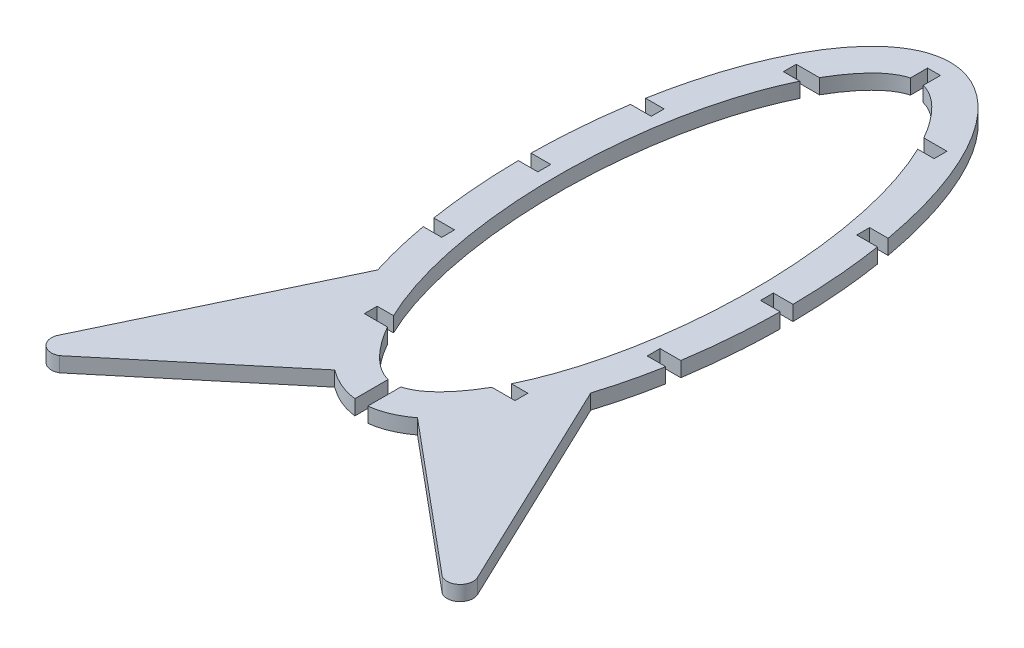
SolidWorks part; units mm, degrees
ref_plane "Front Plane" through (0, 0, 0) normal (0, 0, 1) x (1, 0, 0)
ref_plane "Top Plane" through (0, 0, 0) normal (0, 1, 0) x (1, 0, 0)
ref_plane "Right Plane" through (0, 0, 0) normal (1, 0, 0) x (0, 0, -1)
sketch "Sketch1" plane through (0, 0, 0) normal (0, 1, 0) x (1, 0, 0)
  line L2 (25.4, 0) -> (-45.1447, 0) construction
  line L3 (21.59, 0) -> (30.3971, 0) construction
  line L4 (21.59, 1.2446) -> (25.394, 1.2446)
  line L5 (21.59, 1.2446) -> (21.59, -1.2446)
  line L6 (21.59, -1.2446) -> (25.394, -1.2446)
  line L8 (37.0979, -78.485) -> (8.0291, -54.2196)
  line L9 (40.6569, -75.1899) -> (20.6588, -33.2492)
  line L10 (23.7402, 20.32) -> (29.3413, 20.32) construction
  line L11 (19.9302, 21.5646) -> (23.5224, 21.5646)
  line L12 (19.9302, 21.5646) -> (19.9302, 19.0754)
  line L13 (19.9302, 19.0754) -> (23.9434, 19.0754)
  line L19 (14.0482, 40.64) -> (-23.5224, 40.64) construction
  line L20 (0, 57.15) -> (0, 53.975) construction
  line L21 (-37.0979, -78.485) -> (-8.0291, -54.2196)
  line L22 (-14.6132, -41.8846) -> (-10.1242, -41.8846)
  line L23 (-14.6132, -41.8846) -> (-14.6132, -39.3954)
  line L24 (-14.6132, -39.3954) -> (-11.4313, -39.3954)
  line L25 (19.9302, -21.5646) -> (23.5224, -21.5646)
  line L26 (19.9302, -21.5646) -> (19.9302, -19.0754)
  line L27 (19.9302, -19.0754) -> (23.9434, -19.0754)
  line L28 (-40.6569, -75.1899) -> (-20.6588, -33.2492)
  line L29 (14.6132, 41.8846) -> (10.1242, 41.8846)
  line L30 (14.6132, 41.8846) -> (14.6132, 39.3954)
  line L31 (14.6132, 39.3954) -> (11.4313, 39.3954)
  line L32 (-19.9302, -21.5646) -> (-23.5224, -21.5646)
  line L33 (-19.9302, -21.5646) -> (-19.9302, -19.0754)
  line L34 (-19.9302, -19.0754) -> (-23.9434, -19.0754)
  line L35 (-21.59, 1.2446) -> (-21.59, -1.2446)
  line L36 (-21.59, 1.2446) -> (-25.394, 1.2446)
  line L37 (-21.59, -1.2446) -> (-25.394, -1.2446)
  line L38 (-19.9302, 21.5646) -> (-23.5224, 21.5646)
  line L39 (-19.9302, 21.5646) -> (-19.9302, 19.0754)
  line L40 (-19.9302, 19.0754) -> (-23.9434, 19.0754)
  line L41 (14.6132, -39.3954) -> (11.4313, -39.3954)
  line L42 (-14.6132, 41.8846) -> (-10.1242, 41.8846)
  line L43 (-14.6132, 41.8846) -> (-14.6132, 39.3954)
  line L44 (-14.6132, 39.3954) -> (-11.4313, 39.3954)
  line L46 (0, 39.3954) -> (0, -57.15) construction
  line L47 (14.6132, -41.8846) -> (14.6132, -39.3954)
  line L48 (14.6132, -41.8846) -> (10.1242, -41.8846)
  line L49 (1.2446, -53.975) -> (1.2446, -50.6449)
  line L50 (-1.2446, 53.975) -> (1.2446, 53.975)
  line L51 (-1.2446, 53.975) -> (-1.2446, 50.6449)
  line L53 (1.2446, 53.975) -> (1.2446, 50.6449)
  line L54 (1.2446, -53.975) -> (1.2446, -57.0814)
  line L55 (-1.2446, -53.975) -> (-1.2446, -50.6449)
  line L56 (-1.2446, -53.975) -> (-1.2446, -57.0814)
  arc A0 (37.0979, -78.485) -> (40.6569, -75.1899) centre (38.3642, -76.2831) ccw
  arc A1 (-37.0979, -78.485) -> (-40.6569, -75.1899) centre (-38.3642, -76.2831) cw
  ellipse E0 centre (0, 0) end of major axis (0, 57.15) minor radius 25.4 (-23.9434, 19.0754) -> (-25.394, 1.2446) ccw
  ellipse E1 centre (0, 0) end of major axis (0, 57.15) minor radius 25.4 (-25.394, -1.2446) -> (-23.9434, -19.0754) ccw
  ellipse E2 centre (0, 0) end of major axis (0, 57.15) minor radius 25.4 (-23.5224, -21.5646) -> (-20.6588, -33.2492) ccw
  ellipse E3 centre (0, 0) end of major axis (0, 57.15) minor radius 25.4 (23.9434, -19.0754) -> (25.394, -1.2446) ccw
  ellipse E4 centre (0, 0) end of major axis (0, 57.15) minor radius 25.4 (25.394, 1.2446) -> (23.9434, 19.0754) ccw
  ellipse E5 centre (0, 0) end of major axis (0, 57.15) minor radius 25.4 (23.5224, 21.5646) -> (-23.5224, 21.5646) ccw
  ellipse E6 centre (0, 0) end of major axis (0, 57.15) minor radius 25.4 (1.2446, -57.0814) -> (8.0291, -54.2196) ccw
  ellipse E7 centre (0, 0) end of major axis (0, 57.15) minor radius 25.4 (-8.0291, -54.2196) -> (-1.2446, -57.0814) ccw
  ellipse E8 centre (0, 0) end of major axis (0, 57.15) minor radius 25.4 (20.6588, -33.2492) -> (23.5224, -21.5646) ccw
  spline S0 degree 3 poles (10.1242, 41.8846) (9.6963, 42.6376) (8.1175, 45.2063) (5.3181, 48.5143) (2.7975, 50.1532) (1.5926, 50.559) (1.2446, 50.6449) knots -0.663564 -0.663564 -0.663564 -0.663564 -0.589049 -0.392699 -0.19635 -0.109038 -0.109038 -0.109038 -0.109038
  spline S1 degree 3 poles (1.2446, -50.6449) (1.5926, -50.559) (2.7975, -50.1532) (5.3181, -48.5143) (8.1175, -45.2063) (9.6963, -42.6376) (10.1242, -41.8846) knots -3.032554 -3.032554 -3.032554 -3.032554 -2.945243 -2.748894 -2.552544 -2.478028 -2.478028 -2.478028 -2.478028
  spline S2 degree 3 poles (-1.2446, -50.6449) (-1.5926, -50.559) (-2.7975, -50.1532) (-5.3181, -48.5143) (-8.1175, -45.2063) (-9.6963, -42.6376) (-10.1242, -41.8846) knots -3.032554 -3.032554 -3.032554 -3.032554 -2.945243 -2.748894 -2.552544 -2.478028 -2.478028 -2.478028 -2.478028
  spline S3 degree 3 poles (-10.1242, 41.8846) (-9.6963, 42.6376) (-8.1175, 45.2063) (-5.3181, 48.5143) (-2.7975, 50.1532) (-1.5926, 50.559) (-1.2446, 50.6449) knots -0.663564 -0.663564 -0.663564 -0.663564 -0.589049 -0.392699 -0.19635 -0.109038 -0.109038 -0.109038 -0.109038
  spline S4 degree 3 poles (-11.4313, -39.3954) (-11.6771, -38.8896) (-12.9878, -36.0709) (-15.1482, -30.1662) (-18.0998, -17.7755) (-19.6835, 0) (-18.0998, 17.7755) (-15.1482, 30.1662) (-12.9878, 36.0709) (-11.6771, 38.8896) (-11.4313, 39.3954) knots -2.400746 -2.400746 -2.400746 -2.400746 -2.356194 -2.159845 -1.963495 -1.570796 -1.178097 -0.981748 -0.785398 -0.740847 -0.740847 -0.740847 -0.740847
  spline S5 degree 3 poles (11.4313, -39.3954) (11.6771, -38.8896) (12.9878, -36.0709) (15.1482, -30.1662) (18.0998, -17.7755) (19.6835, 0) (18.0998, 17.7755) (15.1482, 30.1662) (12.9878, 36.0709) (11.6771, 38.8896) (11.4313, 39.3954) knots -2.400746 -2.400746 -2.400746 -2.400746 -2.356194 -2.159845 -1.963495 -1.570796 -1.178097 -0.981748 -0.785398 -0.740847 -0.740847 -0.740847 -0.740847
  point P25 (19.9302, 20.32)
  point P35 (44.1664, -82.55)
  dimension "D5" = 2.54
  dimension "D1" = 114.3
  dimension "D2" = 25.4
  dimension "D4" = 2.4892
  dimension "D6" = 3.81
  dimension "D7" = 2.4892
  dimension "D9" = 3.81
  dimension "D3" = 25.4
  dimension "D10" = 2.4892
  dimension "D8" = 2.4892
  dimension "D11" = 39.8605
  dimension "D12" = 29.2264
  dimension "D13" = 20.32
extrude "Boss-Extrude1" add sketch "Sketch1" along normal blind 2.8956
equation "\"slot_width\"= 0.098"
equation "\"slot_depth\"= 0.15"
equation "\"body_height\"= 4.5"
equation "\"fin_height\"= 1"
equation "\"gap_distance\"= 0.8"
equation "\"D1@Sketch1\"=\"body_height\""
equation "\"D4@Sketch1\"=\"slot_width\""
equation "\"D7@Sketch1\"=\"slot_width\""
equation "\"D10@Sketch1\"=\"slot_width\""
equation "\"D13@Sketch1\"=\"gap_distance\""
equation "\"D3@Sketch1\"=\"fin_height\""
equation "\"D6@Sketch1\"=\"slot_depth\""
equation "\"D9@Sketch1\"=\"slot_depth\""
equation "\"D8@Sketch1\"=\"slot_width\""
